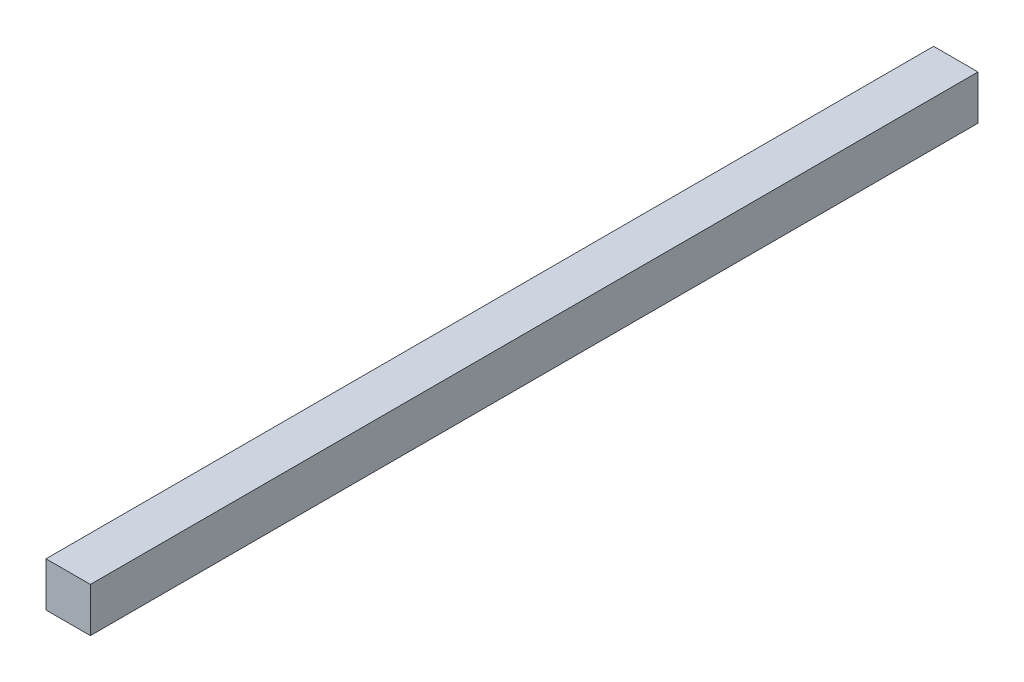
SolidWorks part; units mm, degrees
ref_plane "前视基准面" through (0, 0, 0) normal (0, 0, 1) x (1, 0, 0)
ref_plane "上视基准面" through (0, 0, 0) normal (0, 1, 0) x (1, 0, 0)
ref_plane "右视基准面" through (0, 0, 0) normal (1, 0, 0) x (0, 0, -1)
sketch "草图1" plane through (0, 0, 0) normal (0, 0, 1) x (1, 0, 0)
  line L1 (-5, 5) -> (5, 5)
  line L2 (-5, 5) -> (-5, -5)
  line L3 (-5, -5) -> (5, -5)
  line L4 (5, 5) -> (5, -5)
  line L5 (-5, 5) -> (5, -5) construction
  line L6 (-5, -5) -> (5, 5) construction
  point P0 (0, 0)
  dimension "D1" = 10
  dimension "D2" = 10
extrude "凸台-拉伸1" add sketch "草图1" along normal blind 300 contours L1 L4 L3 L2
sketch "草图2" plane through (0, 0, 0) normal (0, 0, -1) x (-1, 0, 0)
  line L4 (5, -5) -> (5, 5)
  line L5 (5, 5) -> (-5, 5)
  line L6 (-5, 5) -> (-5, -5)
  line L7 (-5, -5) -> (5, -5)
  line L8 (5, -5) -> (5, 5)
  line L9 (5, 5) -> (-5, 5)
  line L10 (-5, 5) -> (-5, -5)
  line L11 (-5, -5) -> (5, -5)
  dimension "D1" = 0
extrude "切除-拉伸1" cut sketch "草图2" against normal blind 100
sketch "草图3" plane through (0, 0, 100) normal (0, 0, -1) x (-1, 0, 0)
  line L1 (-3, 3) -> (3, 3)
  line L2 (-3, 3) -> (-3, -3)
  line L3 (-3, -3) -> (3, -3)
  line L4 (3, 3) -> (3, -3)
  line L5 (-3, 3) -> (3, -3) construction
  line L6 (-3, -3) -> (3, 3) construction
  point P0 (0, 0)
  dimension "D1" = 6
  dimension "D2" = 6
extrude "切除-拉伸-薄壁1" cut sketch "草图3" against normal through all thin thin type one direction wall 10
sketch "草图4" plane through (0, 0, 100) normal (0, 0, -1) x (-1, 0, 0)
  line L1 (-3.495, 3.3272) -> (3.495, 3.3272)
  line L2 (-3.495, 3.3272) -> (-3.495, -3.3272)
  line L3 (-3.495, -3.3272) -> (3.495, -3.3272)
  line L4 (3.495, 3.3272) -> (3.495, -3.3272)
  line L5 (-3.495, 3.3272) -> (3.495, -3.3272) construction
  line L6 (-3.495, -3.3272) -> (3.495, 3.3272) construction
  point P0 (0, 0)
extrude "切除-拉伸2" cut sketch "草图4" against normal blind 80
